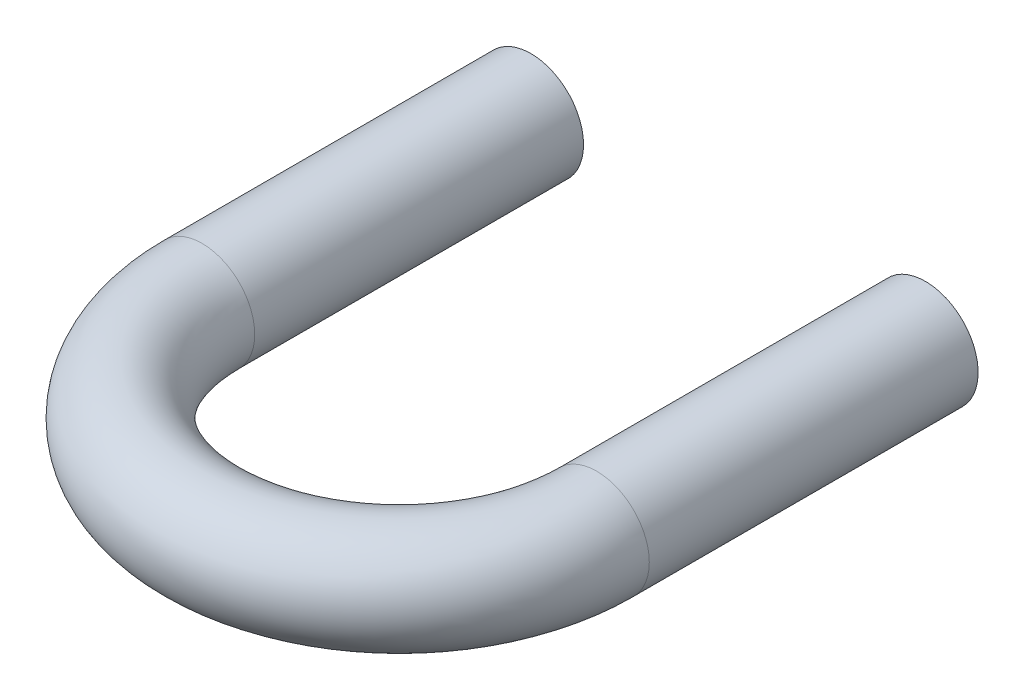
SolidWorks part; units mm, degrees
material "AISI 1020"
ref_plane "Front Plane" through (0, 0, 0) normal (0, 0, 1) x (1, 0, 0)
ref_plane "Top Plane" through (0, 0, 0) normal (0, 1, 0) x (1, 0, 0)
ref_plane "Right Plane" through (0, 0, 0) normal (1, 0, 0) x (0, 0, -1)
sketch "Sketch1" plane through (0, 0, 0) normal (0, 0, 1) x (1, 0, 0)
  circle A1 centre (-15, 0) radius 4
  dimension "D4" = 8
  dimension "D1" = 15
sketch "Sketch2" plane through (0, 0, 0) normal (0, 1, 0) x (1, 0, 0)
  line L0 (-15, 0) -> (-15, -25)
  line L1 (-19, 0) -> (-11, 0) construction
  line L2 (15, -25) -> (15, 0)
  arc A0 (-15, -25) -> (15, -25) centre (0, -25) ccw
  point P6 (0, -14.0192)
  point P8 (0, 0)
  point P10 (0, 0)
  point P11 (0, 0)
  point P12 (7.5, -40)
  point P13 (0, -40)
  dimension "D2" = 15
  dimension "D1" = 25
  dimension "D3" = 15
  dimension "D4" = 15
sweep "Sweep1" add profiles "Sketch1" path "Sketch2"
